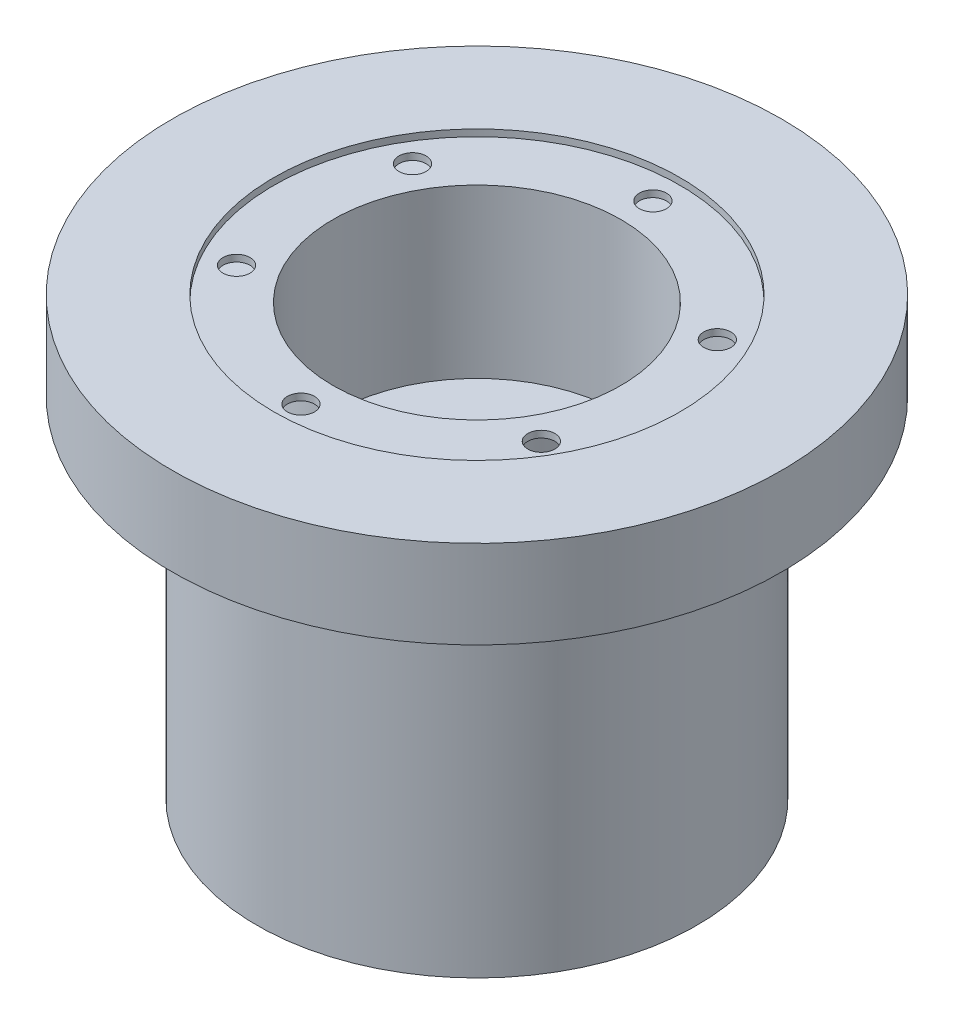
SolidWorks part; units mm, degrees
ref_plane "Front Plane" through (0, 0, 0) normal (0, 0, 1) x (1, 0, 0)
ref_plane "Top Plane" through (0, 0, 0) normal (0, 1, 0) x (1, 0, 0)
ref_plane "Right Plane" through (0, 0, 0) normal (1, 0, 0) x (0, 0, -1)
sketch "Sketch2" plane through (0, 0, 0) normal (0, 0, 1) x (1, 0, 0)
  line L1 (-7.7306, -30.6256) -> (-7.7306, -36.6101)
  line L2 (-7.7306, -30.6256) -> (-7.7306, -21.8867)
  line L3 (-7.7306, -21.8867) -> (-4.7306, -21.8867)
  line L4 (-4.7306, -21.8867) -> (-4.7306, -20.3867)
  line L5 (-4.7306, -20.3867) -> (-0.4949, -3.407)
  line L6 (-0.4949, -3.407) -> (-0.4949, -1.907)
  line L7 (-0.4949, -1.907) -> (-8.4949, -1.907)
  line L11 (-7.7306, -36.6101) -> (-15.7306, -36.6101)
  line L12 (-15.7306, -36.6101) -> (-15.7306, 14.8395)
  line L13 (-15.7306, 14.8395) -> (-28.2306, 14.8395)
  line L14 (14.7694, -26.2561) -> (14.7694, -16.2561)
  line L16 (-8.4949, -1.907) -> (-8.4949, 21.8395)
  line L19 (-28.2306, 23.8395) -> (-8.4949, 23.8395)
  line L20 (-8.4949, 23.8395) -> (-8.4949, 21.8395)
  line L28 (-28.2306, 23.8395) -> (-28.2306, 14.8395)
revolve "Revolve-Thin1" add sketch "Sketch2" angle 360 about L14
sketch "Sketch4" plane through (0, 25.8395, 0) normal (0, 1, 0) x (1, 0, 0)
  circle A0 centre (14.7694, 0) radius 30
extrude "Cut-Extrude3" cut sketch "Sketch4" against normal blind 1
sketch "Sketch5" plane through (0, 25.8395, 0) normal (0, 1, 0) x (1, 0, 0)
  circle A0 centre (14.7694, 26) radius 2
  circle A1 centre (37.286, 13) radius 2
  circle A2 centre (37.286, -13) radius 2
  circle A3 centre (14.7694, -26) radius 2
  circle A4 centre (-7.7473, -13) radius 2
  circle A5 centre (-7.7473, 13) radius 2
  point P17 (14.7694, 0)
  dimension "D1" = 6
extrude "Cut-Extrude4" cut sketch "Sketch5" against normal blind 6 contours A0 | A5 | A4 | A3 | A2 | A1
